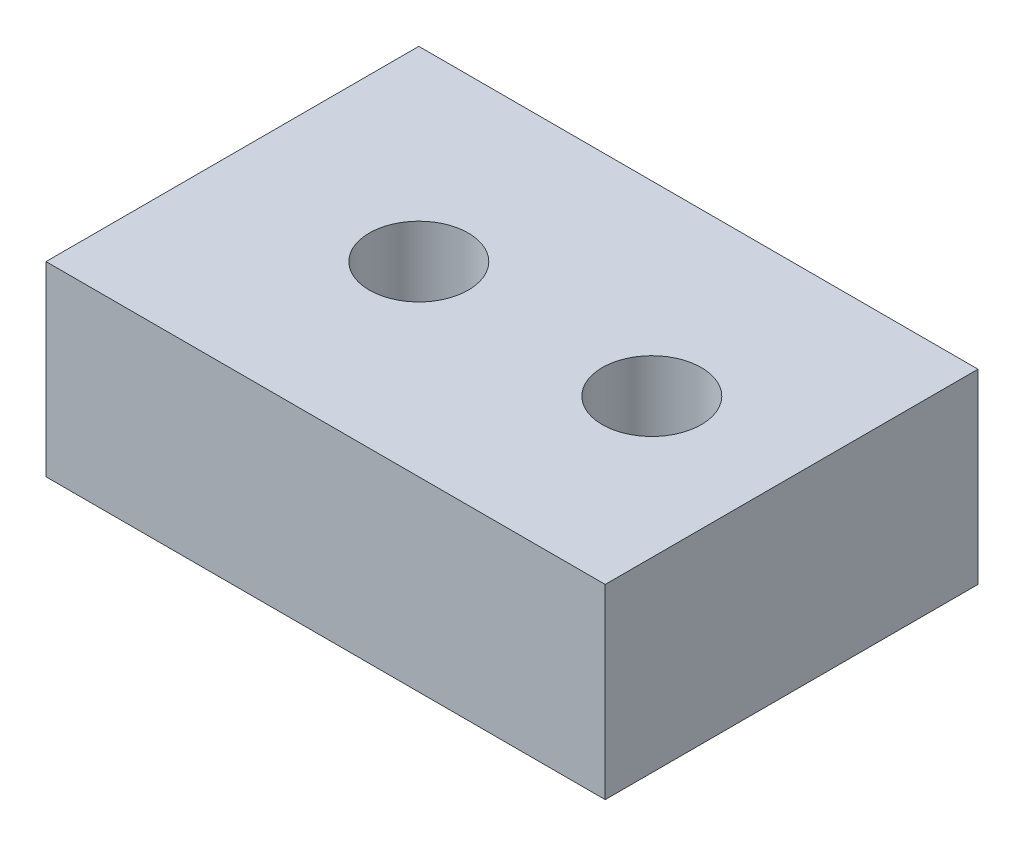
SolidWorks part; units mm, degrees
ref_plane "Front Plane" through (0, 0, 0) normal (0, 0, 1) x (1, 0, 0)
ref_plane "Top Plane" through (0, 0, 0) normal (0, 1, 0) x (1, 0, 0)
ref_plane "Right Plane" through (0, 0, 0) normal (1, 0, 0) x (0, 0, -1)
sketch "Sketch1" plane through (0, 0, 0) normal (0, 1, 0) x (1, 0, 0)
  line L0 (-19.05, 0) -> (19.05, 0) construction
  line L1 (-19.05, -12.7) -> (19.05, -12.7)
  line L2 (-19.05, -12.7) -> (-19.05, 12.7)
  line L3 (-19.05, 12.7) -> (19.05, 12.7)
  line L4 (19.05, -12.7) -> (19.05, 12.7)
  line L5 (-19.05, -12.7) -> (19.05, 12.7) construction
  line L6 (-19.05, 12.7) -> (19.05, -12.7) construction
  circle A0 centre (-6.35, 0) radius 3.3734
  circle A1 centre (9.525, 0) radius 3.3734
  point P0 (0, 0)
  dimension "D3" = 6.7469
  dimension "D1" = 9.525
  dimension "D2" = 15.875
  dimension "D4" = 38.1
  dimension "D5" = 25.4
extrude "Boss-Extrude1" add sketch "Sketch1" along normal blind 12.7
